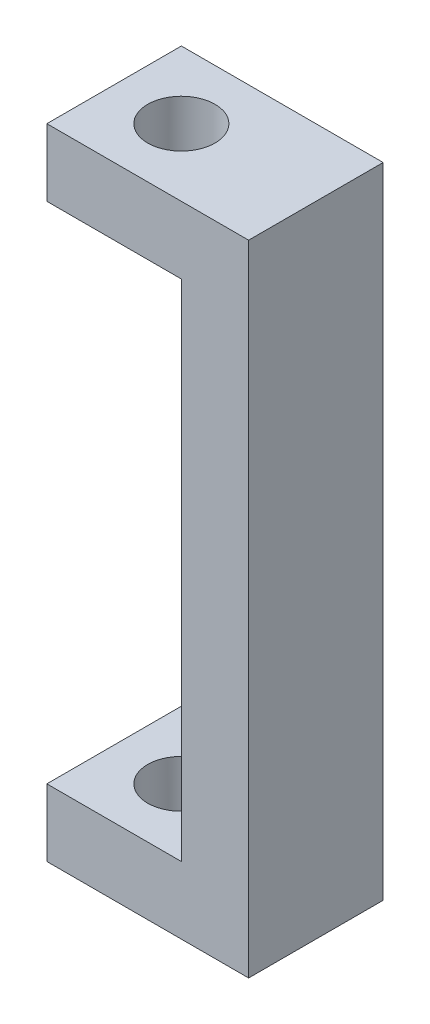
SolidWorks part; units mm, degrees
ref_plane "Front Plane" through (0, 0, 0) normal (0, 0, 1) x (1, 0, 0)
ref_plane "Top Plane" through (0, 0, 0) normal (0, 1, 0) x (1, 0, 0)
ref_plane "Right Plane" through (0, 0, 0) normal (1, 0, 0) x (0, 0, -1)
sketch "Sketch1" plane through (0, 0, 0) normal (0, 0, 1) x (1, 0, 0)
  line L0 (0, 0) -> (12, 0)
  line L1 (12, 0) -> (12, -38)
  line L2 (12, -38) -> (0, -38)
  line L3 (0, -38) -> (0, -34)
  line L4 (0, -34) -> (8, -34)
  line L5 (8, -34) -> (8, -4)
  line L6 (8, -4) -> (0, -4)
  line L7 (0, -4) -> (0, 0)
  dimension "D1" = 30
  dimension "D2" = 4
  dimension "D3" = 4
  dimension "D4" = 12
  dimension "D5" = 8
extrude "Boss-Extrude1" add sketch "Sketch1" along normal blind 8
sketch "Sketch2" plane through (0, 0, 0) normal (0, 1, 0) x (1, 0, 0)
  line L0 (12, 0) -> (0, 0) construction
  line L2 (0, -8) -> (0, 0) construction
  circle A0 centre (4, -4) radius 2
  dimension "D2" = 4
  dimension "D1" = 4
  dimension "D3" = 4
extrude "Cut-Extrude1" cut sketch "Sketch2" against normal blind 38
